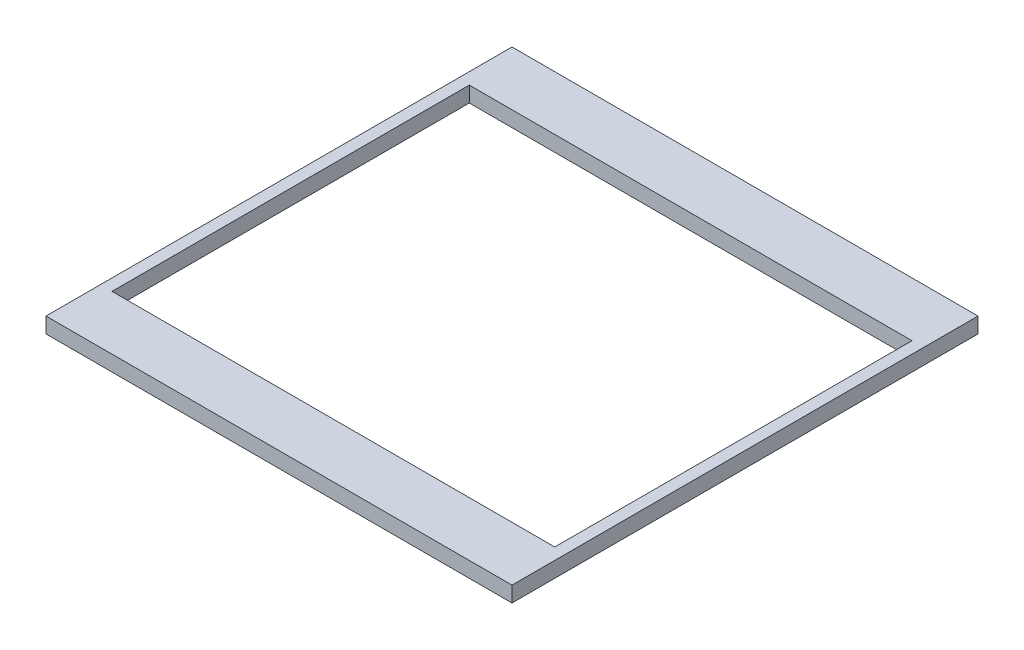
SolidWorks part; units mm, degrees
ref_plane "Front Plane" through (0, 0, 0) normal (0, 0, 1) x (1, 0, 0)
ref_plane "Top Plane" through (0, 0, 0) normal (0, 1, 0) x (1, 0, 0)
ref_plane "Right Plane" through (0, 0, 0) normal (1, 0, 0) x (0, 0, -1)
sketch "Sketch1" plane through (0, 0, 0) normal (0, 1, 0) x (1, 0, 0)
  line L1 (-38.1, -38.1) -> (38.1, -38.1)
  line L2 (-38.1, -38.1) -> (-38.1, 38.1)
  line L3 (-38.1, 38.1) -> (38.1, 38.1)
  line L4 (38.1, -38.1) -> (38.1, 38.1)
  line L5 (-38.1, -38.1) -> (38.1, 38.1) construction
  line L6 (-38.1, 38.1) -> (38.1, -38.1) construction
  point P0 (0, 0)
  dimension "D1" = 76.2
  dimension "D2" = 76.2
extrude "body" add sketch "Sketch1" along normal blind 2.54
sketch "Sketch2" plane through (0, 2.54, 0) normal (0, 1, 0) x (1, 0, 0)
  line L1 (-36.195, -29.21) -> (36.195, -29.21)
  line L2 (-36.195, -29.21) -> (-36.195, 29.21)
  line L3 (-36.195, 29.21) -> (36.195, 29.21)
  line L4 (36.195, -29.21) -> (36.195, 29.21)
  line L5 (-36.195, -29.21) -> (36.195, 29.21) construction
  line L6 (-36.195, 29.21) -> (36.195, -29.21) construction
  point P0 (0, 0)
  dimension "D1" = 72.39
  dimension "D2" = 0
  dimension "D3" = 58.42
  dimension "D4" = 0
extrude "circuitboard hole" cut sketch "Sketch2" against normal blind 2.54
